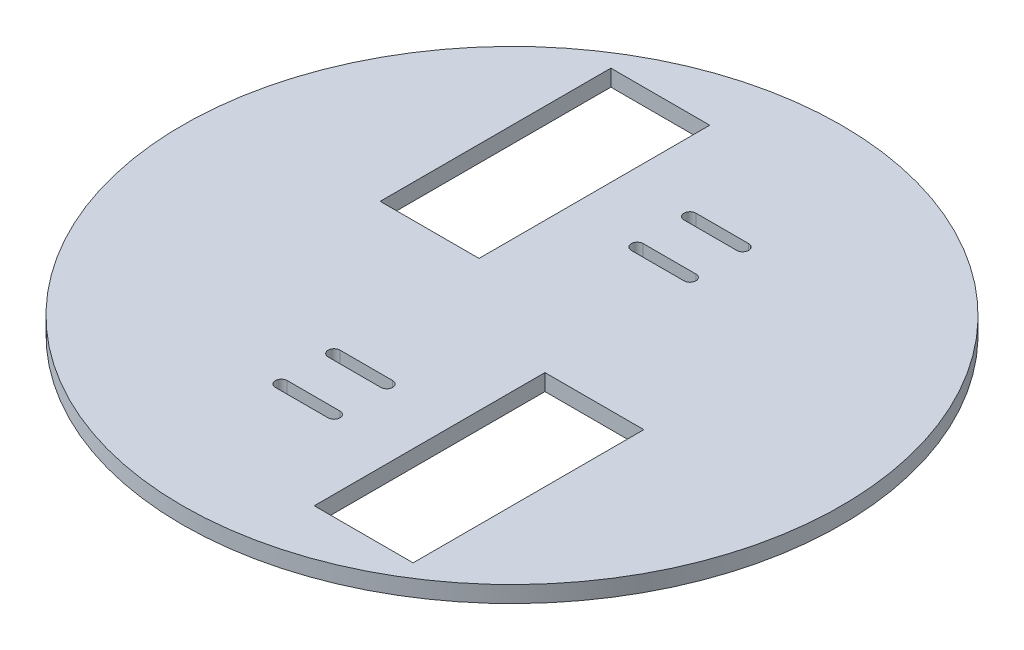
SolidWorks part; units mm, degrees
ref_plane "前视基准面" through (0, 0, 0) normal (0, 0, 1) x (1, 0, 0)
ref_plane "上视基准面" through (0, 0, 0) normal (0, 1, 0) x (1, 0, 0)
ref_plane "右视基准面" through (0, 0, 0) normal (1, 0, 0) x (0, 0, -1)
other "Configuration Table"
sketch "草图1" plane through (0, 0, 0) normal (0, 1, 0) x (1, 0, 0)
  circle A0 centre (0, 0) radius 100
  dimension "D1" = 200
extrude "凸台-拉伸1" add sketch "草图1" along normal blind 5
sketch "草图2" plane through (0, 0, 0) normal (0, 1, 0) x (1, 0, 0)
  line L4 (7, -32) -> (-21, -32) construction
  line L5 (-24, -35) -> (-24, -55) construction
  line L6 (-21, -58) -> (7, -58) construction
  line L7 (7, -58) -> (7, -32) construction
  line L8 (-17, -37) -> (-1, -37) construction
  line L9 (-17, -35.2) -> (-1, -35.2)
  line L10 (-17, -38.8) -> (-1, -38.8)
  line L11 (7, -45) -> (-24, -45) construction
  line L12 (-17, -53) -> (-1, -53) construction
  line L13 (-17, -54.8) -> (-1, -54.8)
  line L14 (-17, -51.2) -> (-1, -51.2)
  arc A6 (-21, -32) -> (-24, -35) centre (-21, -35) ccw construction
  arc A7 (-24, -55) -> (-21, -58) centre (-21, -55) ccw construction
  circle A8 centre (-16, -53) radius 1.75 construction
  circle A9 centre (-16, -37) radius 1.75 construction
  circle A10 centre (-2, -37) radius 1.75 construction
  circle A11 centre (-2, -53) radius 1.75 construction
  arc A12 (-17, -35.2) -> (-17, -38.8) centre (-17, -37) ccw
  arc A13 (-1, -38.8) -> (-1, -35.2) centre (-1, -37) ccw
  arc A14 (-17, -54.8) -> (-17, -51.2) centre (-17, -53) cw
  arc A15 (-1, -51.2) -> (-1, -54.8) centre (-1, -53) cw
  point P19 (-9, -37)
  point P28 (-9, -53)
  dimension "D2" = 9
  dimension "D3" = 3.5
  dimension "D4" = 3.5
  dimension "D5" = 3.5
  dimension "D6" = 3.5
  dimension "D7" = 23
  dimension "D8" = 16
  dimension "D9" = 9
  dimension "D10" = 23
  dimension "D12" = 14
  dimension "D16" = 26
  dimension "D17" = 3
  dimension "D18" = 3
  dimension "D20" = 1.8
  dimension "D23" = 37
  dimension "D24" = 1
  dimension "D1" = 7
  dimension "D11" = 14
  dimension "D13" = 32
  dimension "D14" = 5
  dimension "D15" = 5
  dimension "D19" = 3
  dimension "D21" = 16
  dimension "D22" = 8
sketch "草图3" plane through (0, 0, 0) normal (0, 1, 0) x (1, 0, 0)
  line L1 (20, -80) -> (50, -80)
  line L2 (20, -80) -> (20, -10)
  line L3 (20, -10) -> (50, -10)
  line L4 (50, -80) -> (50, -10)
  dimension "D1" = 70
  dimension "D2" = 30
  dimension "D3" = 10
  dimension "D4" = 50
extrude "切除-拉伸1" cut sketch "草图3" along normal through all
extrude "切除-拉伸2" cut sketch "草图2" along normal through all
pattern_circular "阵列(圆周)1" count 2 every 180 about axis through (0, 0, 0) along (0, 1, 0) of "切除-拉伸1", "切除-拉伸2"
sketch "草图7" plane through (0, 5, 0) normal (0, 1, 0) x (1, 0, 0)
  line L2 (-17, -54.8) -> (-1, -54.8)
  line L3 (-1, -51.2) -> (-17, -51.2)
  line L4 (20, -80) -> (50, -80)
  line L5 (20, -10) -> (20, -80)
  line L6 (50, -10) -> (20, -10)
  line L7 (50, -80) -> (50, -10)
  line L8 (20, -80) -> (50, -80)
  line L9 (20, -10) -> (20, -80)
  line L10 (50, -10) -> (20, -10)
  line L11 (50, -80) -> (50, -10)
  line L12 (-17, -54.8) -> (-1, -54.8)
  line L13 (-1, -51.2) -> (-17, -51.2)
  line L14 (-17, -38.8) -> (-1, -38.8)
  line L15 (-1, -35.2) -> (-17, -35.2)
  line L16 (-17, -38.8) -> (-1, -38.8)
  line L17 (-1, -35.2) -> (-17, -35.2)
  line L18 (17, 38.8) -> (1, 38.8)
  line L19 (1, 35.2) -> (17, 35.2)
  line L20 (17, 38.8) -> (1, 38.8)
  line L21 (1, 35.2) -> (17, 35.2)
  line L22 (17, 54.8) -> (1, 54.8)
  line L23 (1, 51.2) -> (17, 51.2)
  line L24 (17, 54.8) -> (1, 54.8)
  line L25 (1, 51.2) -> (17, 51.2)
  line L28 (-20, 80) -> (-50, 80)
  line L29 (-20, 10) -> (-20, 80)
  line L30 (-50, 10) -> (-20, 10)
  line L31 (-50, 80) -> (-50, 10)
  line L32 (-20, 80) -> (-50, 80)
  line L33 (-20, 10) -> (-20, 80)
  line L34 (-50, 10) -> (-20, 10)
  line L35 (-50, 80) -> (-50, 10)
  arc A2 (-17, -51.2) -> (-17, -54.8) centre (-17, -53) ccw
  arc A3 (-1, -54.8) -> (-1, -51.2) centre (-1, -53) ccw
  arc A4 (-17, -51.2) -> (-17, -54.8) centre (-17, -53) ccw
  arc A5 (-1, -54.8) -> (-1, -51.2) centre (-1, -53) ccw
  arc A6 (-17, -35.2) -> (-17, -38.8) centre (-17, -37) ccw
  arc A7 (-1, -38.8) -> (-1, -35.2) centre (-1, -37) ccw
  arc A8 (-17, -35.2) -> (-17, -38.8) centre (-17, -37) ccw
  arc A9 (-1, -38.8) -> (-1, -35.2) centre (-1, -37) ccw
  arc A10 (17, 35.2) -> (17, 38.8) centre (17, 37) ccw
  arc A11 (1, 38.8) -> (1, 35.2) centre (1, 37) ccw
  arc A12 (17, 35.2) -> (17, 38.8) centre (17, 37) ccw
  arc A13 (1, 38.8) -> (1, 35.2) centre (1, 37) ccw
  arc A14 (17, 51.2) -> (17, 54.8) centre (17, 53) ccw
  arc A15 (1, 54.8) -> (1, 51.2) centre (1, 53) ccw
  arc A16 (17, 51.2) -> (17, 54.8) centre (17, 53) ccw
  arc A17 (1, 54.8) -> (1, 51.2) centre (1, 53) ccw
  dimension "D1" = 0
  dimension "D2" = 0
  dimension "D3" = 0
  dimension "D4" = 0
  dimension "D5" = 0
  dimension "D6" = 0
